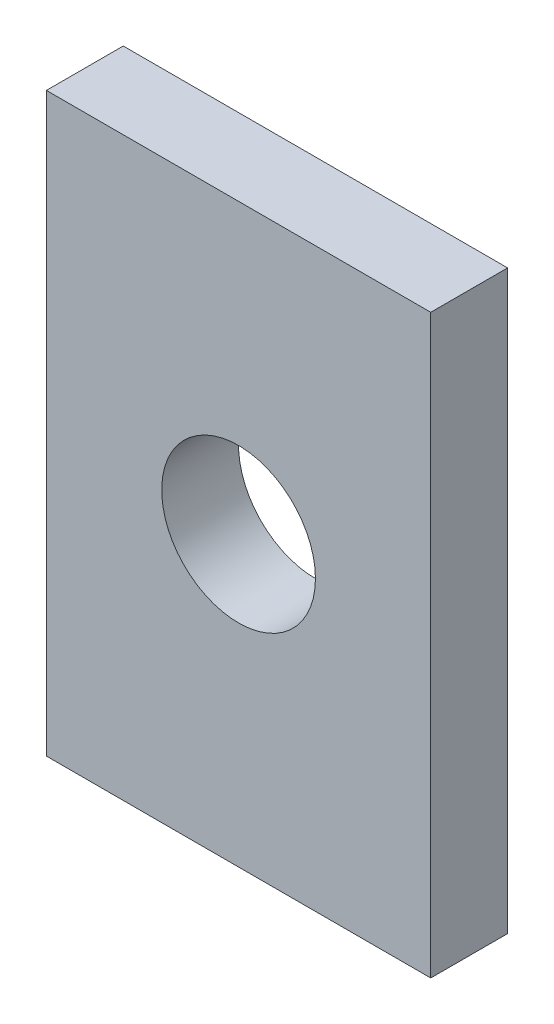
SolidWorks part; units mm, degrees
ref_plane "Front Plane" through (0, 0, 0) normal (0, 0, 1) x (1, 0, 0)
ref_plane "Top Plane" through (0, 0, 0) normal (0, 1, 0) x (1, 0, 0)
ref_plane "Right Plane" through (0, 0, 0) normal (1, 0, 0) x (0, 0, -1)
sketch "Sketch1" plane through (0, 0, 0) normal (0, 0, 1) x (1, 0, 0)
  line L1 (-20, -30) -> (20, -30)
  line L2 (-20, -30) -> (-20, 30)
  line L3 (-20, 30) -> (20, 30)
  line L4 (20, -30) -> (20, 30)
  line L5 (-20, -30) -> (20, 30) construction
  line L6 (-20, 30) -> (20, -30) construction
  circle A0 centre (0, 0) radius 8
  point P0 (0, 0)
  dimension "D3" = 16
  dimension "D1" = 60
  dimension "D2" = 40
extrude "Boss-Extrude1" add sketch "Sketch1" along normal blind 8
